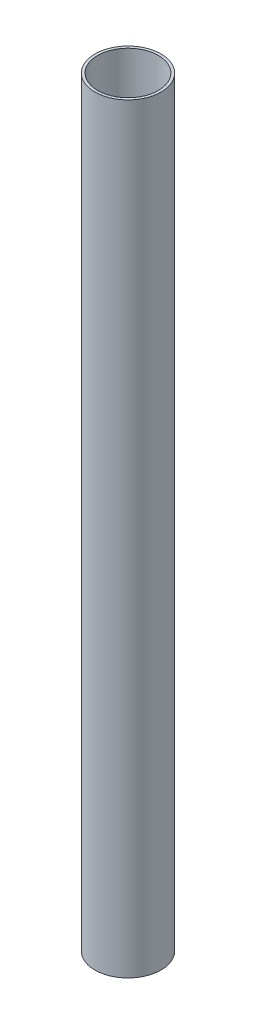
SolidWorks part; units mm, degrees
ref_plane "Front Plane" through (0, 0, 0) normal (0, 0, 1) x (1, 0, 0)
ref_plane "Top Plane" through (0, 0, 0) normal (0, 1, 0) x (1, 0, 0)
ref_plane "Right Plane" through (0, 0, 0) normal (1, 0, 0) x (0, 0, -1)
sketch "Sketch1" plane through (0, 0, 0) normal (0, 1, 0) x (1, 0, 0)
  circle A0 centre (0, 0) radius 0.62
  circle A1 centre (0, 0) radius 0.57
extrude "Boss-Extrude1" add sketch "Sketch1" along normal blind 14.27
